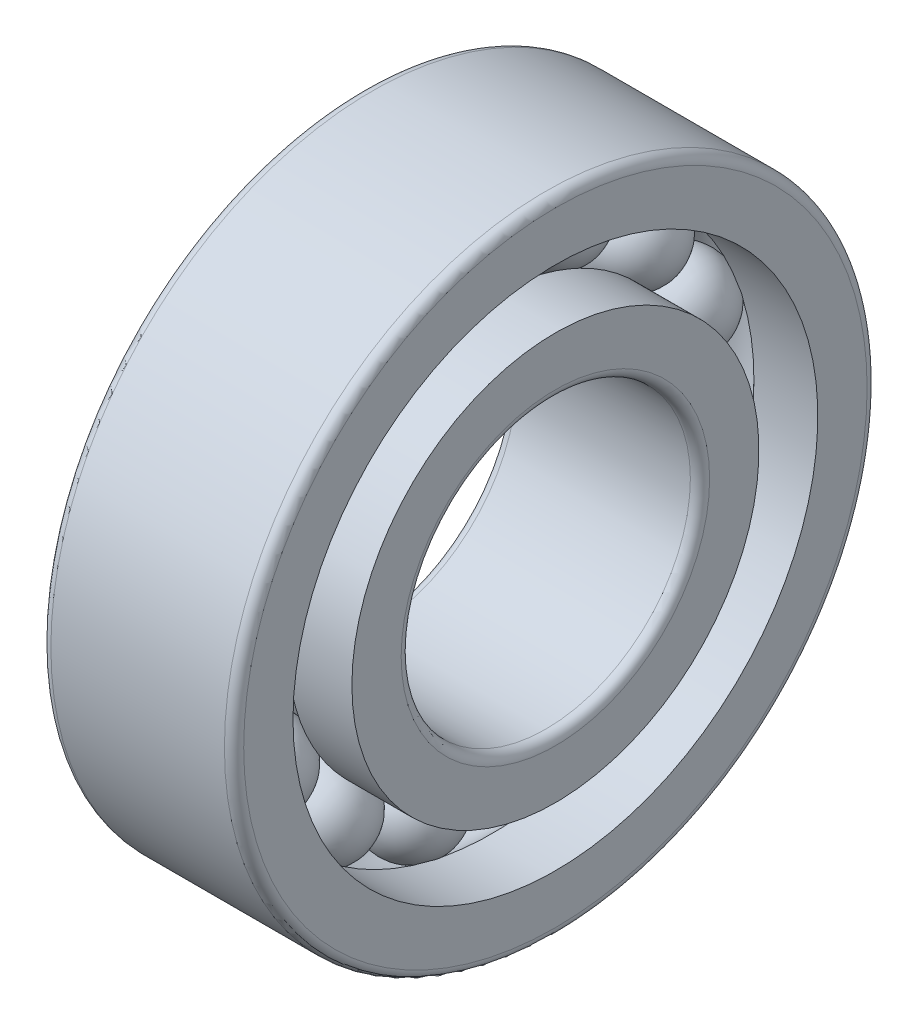
SolidWorks part; units mm, degrees
ref_plane "Front" through (0, 0, 0) normal (0, 0, 1) x (1, 0, 0)
ref_plane "Top" through (0, 0, 0) normal (0, 1, 0) x (1, 0, 0)
ref_plane "Right" through (0, 0, 0) normal (1, 0, 0) x (0, 0, -1)
sketch "Sketch1" plane through (0, 0, 0) normal (0, 0, 1) x (1, 0, 0)
  line L0 (-9.6833, 0) -> (9.8371, 0) construction
  line L1 (-1.375, 7.25) -> (1.375, 7.25)
  line L2 (-4.5966, 7.25) -> (4.6657, 7.25) construction
  arc A0 (1.375, 7.25) -> (-1.375, 7.25) centre (0, 7.25) ccw
  dimension "dia" = 2.75
  dimension "d0" = 14.5
revolve "Revolve1" add sketch "Sketch1" angle 360 about L2
sketch "Sketch2" plane through (0, 0, 0) normal (0, 0, 1) x (1, 0, 0)
  line L0 (-3, 6.3333) -> (-3, 4.5)
  line L1 (-3, 4.5) -> (3, 4.5)
  line L2 (3, 4.5) -> (3, 6.3333)
  line L3 (3, 6.3333) -> (1.0114, 6.3333)
  line L4 (-6.9714, 0) -> (8.1665, 0) construction
  line L5 (-6.7058, 7.25) -> (6.7058, 7.25) construction
  line L6 (-1.0114, 6.3333) -> (-3, 6.3333)
  arc A0 (-1.0114, 6.3333) -> (1.0114, 6.3333) centre (0, 7.25) ccw
  dimension "B" = 6
  dimension "B/2" = 3
  dimension "D5" = 2.73
  dimension "d" = 9
  dimension "D3" = 7.25
  dimension "D4" = 1.8333
revolve "Revolve2" add sketch "Sketch2" angle 360 about L4
sketch "Sketch3" plane through (0, 0, 0) normal (0, 0, 1) x (1, 0, 0)
  line L0 (-8.7107, 0) -> (9.1288, 0) construction
  line L1 (-3, 10) -> (3, 10)
  line L2 (-3, 10) -> (-3, 8.1667)
  line L3 (-3, 8.1667) -> (-1.0114, 8.1667)
  line L4 (3, 10) -> (3, 8.1667)
  line L5 (-7.2948, 7.25) -> (7.2948, 7.25) construction
  line L6 (1.0114, 8.1667) -> (3, 8.1667)
  arc A0 (1.0114, 8.1667) -> (-1.0114, 8.1667) centre (0, 7.25) ccw
  dimension "D1" = 2.73
  dimension "DD" = 20
  dimension "B" = 6
  dimension "D4" = 7.25
  dimension "D5" = 1.8333
  dimension "B/2" = 3
revolve "Revolve3" add sketch "Sketch3" angle 360 about L0
pattern_circular "Circular-Pattern1" count 15 over 360 about axis through (0, 0, 0) along (1, 0, 0) of "Revolve1"
fillet "Fillet1" radius 0.3 4 edges at (-3, 0, 4.5) (-3, 0, 10) (3, 0, 10) (3, 0, 4.5)
equation "\"d0@Sketch1\" = ( \"DD@Sketch3\" + \"d@Sketch2\" )  / 2"
equation "\"dia@Sketch1\" =  ( \"DD@Sketch3\" - \"d@Sketch2\" )  / 4"
equation "\"D3@Sketch2\" = ( \"DD@Sketch3\" + \"d@Sketch2\" )  / 2 / 2"
equation "\"D4@Sketch2\" = ( \"DD@Sketch3\" - \"d@Sketch2\" )  / 6"
equation "\"D5@Sketch2\" = \"dia@Sketch1\" - 0.02"
equation "\"B/2@Sketch2\" = \"B@Sketch2\" / 2"
equation "\"D4@Sketch3\" = ( \"DD@Sketch3\" + \"d@Sketch2\" )  / 2 / 2"
equation "\"D5@Sketch3\" = ( \"DD@Sketch3\" - \"d@Sketch2\" )  / 6"
equation "\"B@Sketch3\" = \"B@Sketch2\""
equation "\"B/2@Sketch3\" = \"B@Sketch3\" / 2"
equation "\"D1@Sketch3\" = \"dia@Sketch1\" - 0.02"
equation "\"m@Circular-Pattern1\" = int( 3.14159265 / atn(( \"dia@Sketch1\" / 2) / sqr(( \"DD@Sketch3\" + \"d@Sketch2\" )  / 2 * ( \"DD@Sketch3\" + \"d@Sketch2\" )  / 2/4 - ( \"dia@Sketch1\" / 2) *  ( \"dia@Sketch1\" / 2))))-1"
